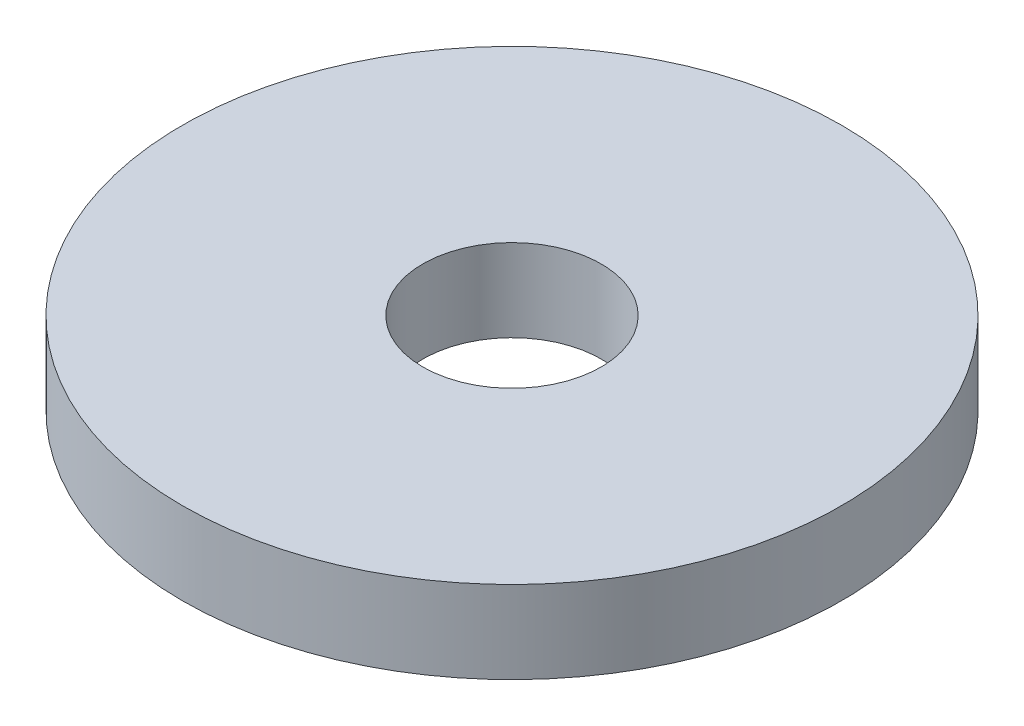
SolidWorks part; units mm, degrees
ref_plane "Plano frontal" through (0, 0, 0) normal (0, 0, 1) x (1, 0, 0)
ref_plane "Plano superior" through (0, 0, 0) normal (0, 1, 0) x (1, 0, 0)
ref_plane "Plano direito" through (0, 0, 0) normal (1, 0, 0) x (0, 0, -1)
sketch "Sketch1" plane through (0, 0, 0) normal (0, 1, 0) x (1, 0, 0)
  circle A0 centre (0, 0) radius 12
  circle A1 centre (0, 0) radius 3.25
  dimension "D1" = 24
  dimension "D2" = 6.5
extrude "Boss-Extrude1" add sketch "Sketch1" along normal mid plane 3
